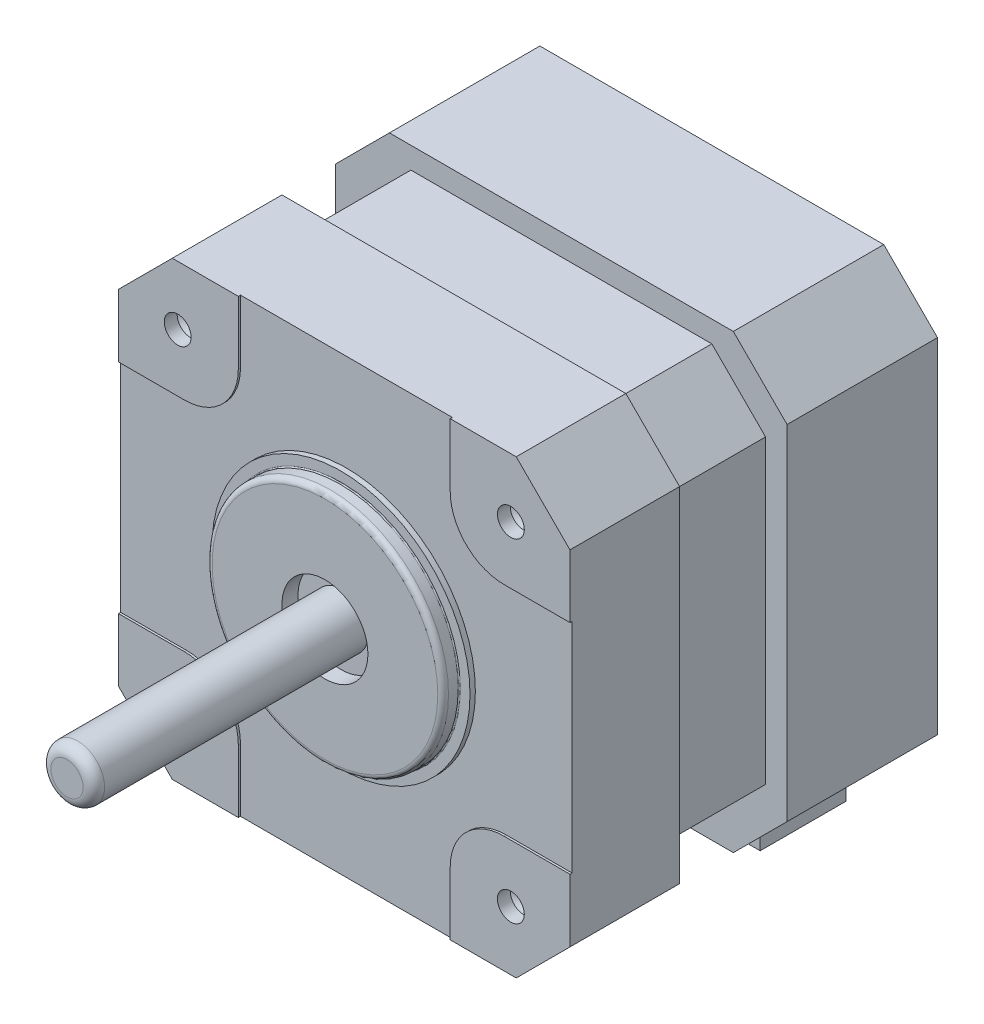
SolidWorks part; units mm, degrees
ref_plane "Front" through (0, 0, 0) normal (0, 0, 1) x (1, 0, 0)
ref_plane "Top" through (0, 0, 0) normal (0, 1, 0) x (1, 0, 0)
ref_plane "Right" through (0, 0, 0) normal (1, 0, 0) x (0, 0, -1)
sketch "Sketch1" plane through (0, 0, 0) normal (0, 0, 1) x (1, 0, 0)
  line L1 (-21, 21) -> (21, 21)
  line L2 (-21, 21) -> (-21, -21)
  line L3 (-21, -21) -> (21, -21)
  line L4 (21, 21) -> (21, -21)
  line L5 (-21, 21) -> (21, -21) construction
  line L6 (-21, -21) -> (21, 21) construction
  point P0 (0, 0)
extrude "Boss-Extrude1" add sketch "Sketch1" along normal blind 36
sketch "Sketch2" plane through (0, 0, 36) normal (0, 0, 1) x (1, 0, 0)
  circle A0 centre (0, 0) radius 11
extrude "Cut-Extrude1" cut sketch "Sketch2" against normal blind 2 flip side to cut
fillet "Fillet1" radius 0.5 1 edges at (11, 0, 36)
sketch "Sketch3" plane through (0, 0, 36) normal (0, 0, 1) x (1, 0, 0)
  circle A0 centre (0, 0) radius 4
extrude "Cut-Extrude2" cut sketch "Sketch3" against normal blind 3
sketch "Sketch4" plane through (0, 0, 33) normal (0, 0, 1) x (1, 0, 0)
  circle A0 centre (0, 0) radius 2.5
extrude "Boss-Extrude2" add sketch "Sketch4" along normal blind 27
fillet "Fillet3" radius 1 1 edges at (2.5, 0, 60)
sketch "Sketch5" plane through (0, 0, 34) normal (0, 0, 1) x (1, 0, 0)
  circle A0 centre (0, 0) radius 12
extrude "Boss-Extrude3" add sketch "Sketch5" along normal blind 0.5
fillet "Fillet4" radius 0.1 1 edges at (11, 0, 34.5)
sketch "Sketch6" plane through (0, 0, 34) normal (0, 0, 1) x (1, 0, 0)
  line L0 (21, 21) -> (-21, 21) construction
  line L1 (-15.5, -15.5) -> (15.5, -15.5)
  line L2 (-15.5, -15.5) -> (-15.5, 15.5)
  line L3 (-15.5, 15.5) -> (15.5, 15.5)
  line L4 (15.5, -15.5) -> (15.5, 15.5)
  line L5 (-15.5, -15.5) -> (15.5, 15.5) construction
  line L6 (-15.5, 15.5) -> (15.5, -15.5) construction
  line L7 (-21, 21) -> (-21, -21) construction
  point P0 (0, 0)
  dimension "D1" = 5.5
  dimension "D2" = 5.5
hole_wizard "M3 Tapped Hole1" positions "Sketch8" profile "Sketch7" tap size "M3" standard "ISO"
sketch "Sketch8" plane through (0, 0, 34) normal (0, 0, 1) x (1, 0, 0)
  point P0 (15.5, 15.5)
  point P3 (-15.5, 15.5)
  point P6 (15.5, -15.5)
  point P9 (-15.5, -15.5)
sketch "Sketch7" plane through (15.5, 15.5, 34) normal (1, 0, 0) x (0, -1, 0)
  line L0 (0, 0) -> (0, 1.7511)
  line L1 (0, 1.7511) -> (1.25, 1)
  line L2 (1.25, 1) -> (1.25, 0)
  line L5 (1.25, 0) -> (0, 0)
  line L10 (0, 1.7511) -> (-1.25, 1) construction
  line L11 (0, -6.35) -> (0, 107.95) construction
  dimension "Tap Drill Dia." = 2.5
  dimension "Tap Drill Depth" = 1
  dimension "Drill Angle" = 118
cosmetic thread "Hole Thread16" parameters "D1"=0, "D2"=3.5
cosmetic thread "Hole Thread17" parameters "D1"=0, "D2"=3.5
cosmetic thread "Hole Thread18" parameters "D1"=0, "D2"=3.5
cosmetic thread "Hole Thread19" parameters "D1"=0, "D2"=3.5
chamfer "Chamfer2" distance 5 angle 45 4 edges at (21, -21, 17) (-21, -21, 17) (-21, 21, 17) (21, 21, 17)
sketch "Sketch9" plane through (0, 0, 34) normal (0, 0, 1) x (1, 0, 0)
  line L0 (16, 21) -> (21, 16)
  line L1 (14.8583, 10.1381) -> (21, 10.1381)
  line L2 (9.8583, 15.1381) -> (9.8583, 21)
  line L3 (9.8583, 21) -> (16, 21)
  line L4 (21, 10.1381) -> (21, 16)
  line L5 (9.8583, 10.1381) -> (18.5763, 18.4237) construction
  line L6 (9.8583, 21) -> (21, 10.1381) construction
  line L7 (0, 21) -> (0, -21) construction
  line L8 (16, 21) -> (-16, 21) construction
  line L9 (-16, -21) -> (16, -21) construction
  line L10 (-9.8583, 21) -> (-21, 10.1381) construction
  line L11 (-9.8583, 10.1381) -> (-18.5763, 18.4237) construction
  line L12 (-21, 10.1381) -> (-21, 16)
  line L13 (-9.8583, 21) -> (-16, 21)
  line L14 (-9.8583, 15.1381) -> (-9.8583, 21)
  line L15 (-14.8583, 10.1381) -> (-21, 10.1381)
  line L16 (-16, 21) -> (-21, 16)
  line L17 (21, 0) -> (-21, 0) construction
  line L18 (21, -16) -> (21, 16) construction
  line L19 (-21, 16) -> (-21, -16) construction
  line L21 (-9.8583, -10.1381) -> (-18.5763, -18.4237) construction
  line L22 (-9.8583, -21) -> (-21, -10.1381) construction
  line L23 (-16, -21) -> (-21, -16)
  line L24 (-14.8583, -10.1381) -> (-21, -10.1381)
  line L25 (-9.8583, -15.1381) -> (-9.8583, -21)
  line L26 (-9.8583, -21) -> (-16, -21)
  line L27 (-21, -10.1381) -> (-21, -16)
  line L28 (9.8583, -21) -> (21, -10.1381) construction
  line L29 (9.8583, -10.1381) -> (18.5763, -18.4237) construction
  line L30 (21, -10.1381) -> (21, -16)
  line L31 (9.8583, -21) -> (16, -21)
  line L32 (9.8583, -15.1381) -> (9.8583, -21)
  line L33 (14.8583, -10.1381) -> (21, -10.1381)
  line L34 (16, -21) -> (21, -16)
  arc A0 (14.8583, 10.1381) -> (9.8583, 15.1381) centre (14.8583, 15.1381) cw
  arc A1 (-14.8583, 10.1381) -> (-9.8583, 15.1381) centre (-14.8583, 15.1381) ccw
  arc A2 (-14.8583, -10.1381) -> (-9.8583, -15.1381) centre (-14.8583, -15.1381) cw
  arc A3 (14.8583, -10.1381) -> (9.8583, -15.1381) centre (14.8583, -15.1381) ccw
  point P0 (15.5, 15.5)
  point P28 (-15.5, 15.5)
  point P46 (-15.5, -15.5)
  point P56 (15.5, -15.5)
  dimension "D1" = 5
extrude "Boss-Extrude4" add sketch "Sketch9" along normal blind 0.2
sketch "Sketch10" plane through (0, 0, 34) normal (0, 0, 1) x (1, 0, 0)
  line L0 (21, 16.0179) -> (16.0179, 21)
  line L1 (-21, -16.0502) -> (-21, 16.0179)
  line L2 (-21, 16.0179) -> (-15.9803, 21.0376)
  line L3 (-16.0502, -21) -> (16.0108, -21)
  line L4 (21, 16.0179) -> (21, -16.0108)
  line L5 (-18.4407, 18.4407) -> (18.5054, -18.5054) construction
  line L6 (-18.5251, -18.5251) -> (18.509, 18.509) construction
  line L7 (16.0108, -21) -> (21, -16.0108)
  line L8 (-15.9803, 21.0376) -> (16.0179, 21)
  line L9 (-16.0502, -21) -> (-21, -16.0502)
  line L10 (19, -14) -> (14, -19)
  line L11 (14, 19) -> (-14, 19)
  line L12 (19, 14) -> (19, -14)
  line L13 (14, -19) -> (-14, -19)
  line L14 (-19, 14) -> (-19, -14)
  line L15 (19, 19) -> (-19, -19) construction
  line L16 (19, -19) -> (-19, 19) construction
  line L17 (19, 14) -> (14, 19)
  line L18 (-14, 19) -> (-19, 14)
  line L19 (-19, -14) -> (-14, -19)
  point P0 (0, 0)
  point P4 (0, 0)
extrude "Cut-Extrude4" cut sketch "Sketch10" against normal blind 10 from offset 10 offset against normal yes
sketch "Sketch13" plane through (0, 0, 34.2) normal (0, 0, 1) x (1, 0, 0)
  line L0 (-9.8583, -21) -> (9.8583, -21) construction
  line L1 (-12.5, -25.6) -> (12.5, -25.6)
  line L2 (-12.5, -25.6) -> (-12.5, -23.3)
  line L3 (-13.7, -23.3) -> (-16, -21)
  line L4 (12.5, -25.6) -> (12.5, -23.3)
  line L5 (-12.5, -25.6) -> (0, -21) construction
  line L6 (0, -21) -> (12.5, -25.6) construction
  line L7 (12.5, -21) -> (-12.5, -21)
  line L10 (-12.5, -21) -> (-16, -21)
  line L11 (-12.5, -23.3) -> (-13.7, -23.3)
  line L12 (12.5, -23.3) -> (13.7, -23.3)
  line L13 (12.5, -21) -> (16, -21)
  line L14 (16, -21) -> (13.7, -23.3)
  point P0 (0, -21)
extrude "Boss-Extrude5" add sketch "Sketch13" along normal blind 8 from offset 34.2 offset against normal yes
hole_wizard "M3 Tapped Hole3" positions "Sketch17" profile "Sketch16" tap size "M3" standard "ISO"
sketch "Sketch17" plane through (0, 0, 34.2) normal (0, 0, 1) x (1, 0, 0)
  point P18 (-15.5, 15.5)
  point P21 (15.5, 15.5)
  point P24 (15.5, -15.5)
  point P27 (-15.5, -15.5)
sketch "Sketch16" plane through (-15.5, 15.5, 34.2) normal (1, 0, 0) x (0, -1, 0)
  line L0 (0, 0) -> (0, 1.7511)
  line L1 (0, 1.7511) -> (1.25, 1)
  line L2 (1.25, 1) -> (1.25, 0)
  line L5 (1.25, 0) -> (0, 0)
  line L10 (0, 1.7511) -> (-1.25, 1) construction
  line L11 (0, -6.35) -> (0, 107.95) construction
  dimension "Tap Drill Dia." = 2.5
  dimension "Tap Drill Depth" = 1
  dimension "Drill Angle" = 118
cosmetic thread "Hole Thread9" parameters "D1"=1, "D2"=3
cosmetic thread "Hole Thread13" parameters "D1"=1, "D2"=3
cosmetic thread "Hole Thread14" parameters "D1"=1, "D2"=3
cosmetic thread "Hole Thread15" parameters "D1"=1, "D2"=3
sketch "Sketch18" plane through (0, 0, 0) normal (0, 0, -1) x (-1, 0, 0)
  line L0 (-16, 21) -> (16, 21) construction
  point P0 (0, 21)
